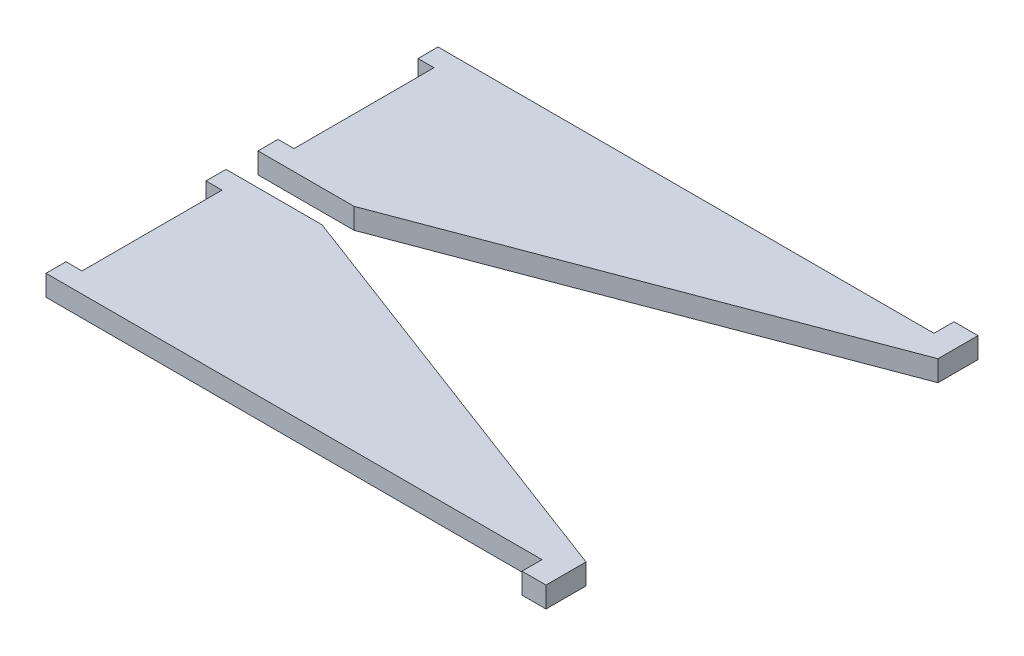
SolidWorks part; units mm, degrees
material "6061 Alloy"
ref_plane "Front Plane" through (0, 0, 0) normal (0, 0, 1) x (1, 0, 0)
ref_plane "Top Plane" through (0, 0, 0) normal (0, 1, 0) x (1, 0, 0)
ref_plane "Right Plane" through (0, 0, 0) normal (1, 0, 0) x (0, 0, -1)
sketch "Sketch1" plane through (0, 0, 0) normal (0, 1, 0) x (1, 0, 0)
  line L1 (157.48, 0) -> (157.48, 6.35)
  line L2 (157.48, 6.35) -> (165.1, 6.35)
  line L3 (165.1, 6.35) -> (165.1, -6.35)
  line L4 (165.1, -6.35) -> (30.48, -57.15)
  line L5 (5.08, -50.8) -> (5.08, -6.35)
  line L10 (0, -6.35) -> (5.08, -6.35)
  line L11 (0, 0) -> (0, -6.35)
  line L12 (0, 0) -> (157.48, 0)
  line L13 (30.48, -57.15) -> (0, -57.15)
  line L14 (0, -57.15) -> (0, -50.8)
  line L15 (0, -50.8) -> (5.08, -50.8)
  line L16 (-11.8226, -62.23) -> (49988.1774, -62.23) construction
  line L17 (0, -73.66) -> (5.08, -73.66)
  line L18 (0, -67.31) -> (0, -73.66)
  line L19 (30.48, -67.31) -> (0, -67.31)
  line L20 (0, -124.46) -> (157.48, -124.46)
  line L21 (0, -124.46) -> (0, -118.11)
  line L22 (0, -118.11) -> (5.08, -118.11)
  line L23 (5.08, -73.66) -> (5.08, -118.11)
  line L24 (165.1, -118.11) -> (30.48, -67.31)
  line L25 (165.1, -130.81) -> (165.1, -118.11)
  line L26 (157.48, -130.81) -> (165.1, -130.81)
  line L27 (157.48, -124.46) -> (157.48, -130.81)
  line L29 (0.3666, -135.89) -> (165.4666, -135.89) construction
  line L30 (0.3666, -135.89) -> (0.3666, 11.43) construction
  line L31 (0.3666, 11.43) -> (165.4666, 11.43) construction
  line L32 (165.4666, -135.89) -> (165.4666, 11.43) construction
  line L33 (0.3666, -135.89) -> (165.4666, 11.43) construction
  line L34 (0.3666, 11.43) -> (165.4666, -135.89) construction
  line L35 (165.4666, -24.638) -> (132.4466, -24.638) construction
  line L36 (165.4666, -24.638) -> (165.4666, -99.695) construction
  line L37 (165.4666, -99.695) -> (132.4466, -99.695) construction
  line L38 (132.4466, -24.638) -> (132.4466, -99.695) construction
  point P26 (82.9166, -62.23)
  dimension "D1" = 165.1
  dimension "D2" = 5.08
  dimension "D3" = 25.4
  dimension "D4" = 152.4
  dimension "D5" = 6.35
  dimension "D6" = 6.35
  dimension "D7" = 63.5
  dimension "D8" = 6.35
  dimension "D9" = 5.08
  dimension "D10" = 147.32
  dimension "D11" = 36.068
  dimension "D12" = 36.195
  dimension "D13" = 33.02
  dimension "D14" = 165.1
extrude "Boss-Extrude1" add sketch "Sketch1" along normal blind 6.604
